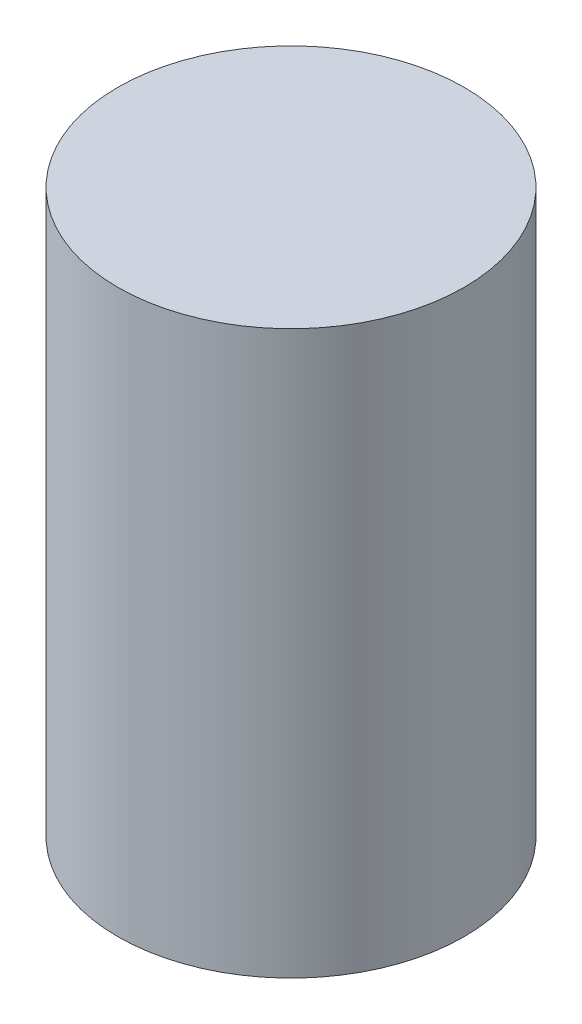
SolidWorks part; units mm, degrees
ref_plane "Front" through (0, 0, 0) normal (0, 0, 1) x (1, 0, 0)
ref_plane "Top" through (0, 0, 0) normal (0, 1, 0) x (1, 0, 0)
ref_plane "Right" through (0, 0, 0) normal (1, 0, 0) x (0, 0, -1)
sketch "Sketch1" plane through (0, 0, 0) normal (0, 1, 0) x (1, 0, 0)
  circle A0 centre (0, 0) radius 7.7
  dimension "D1" = 15.4
extrude "Boss-Extrude1" add sketch "Sketch1" along normal blind 25
